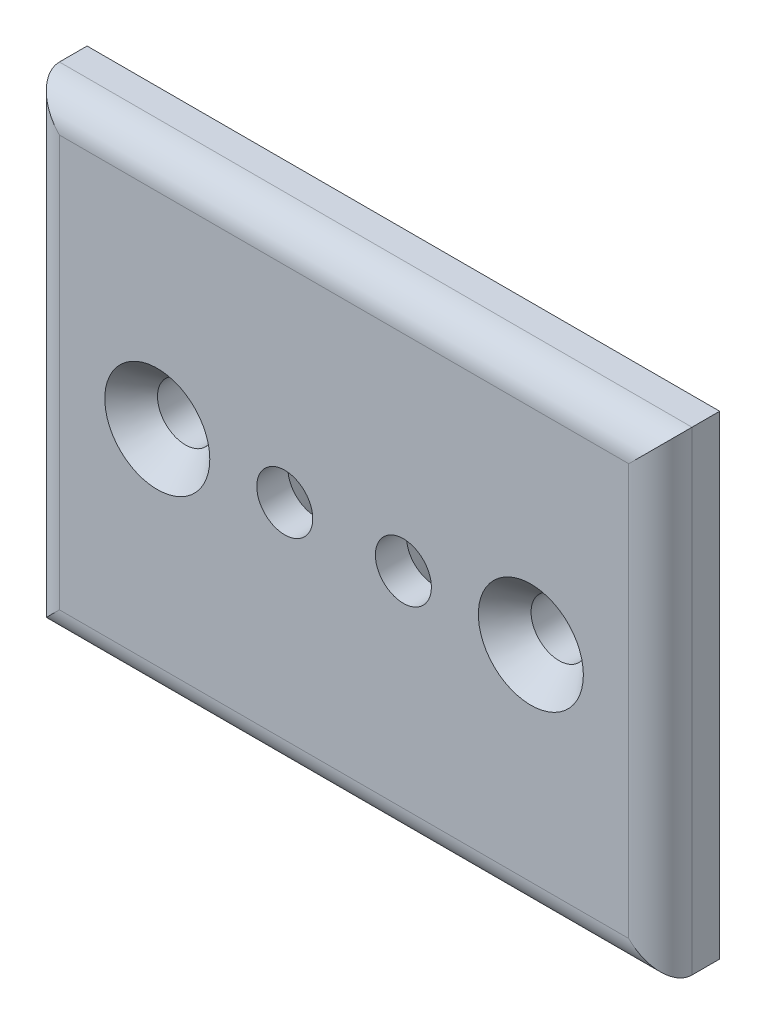
SolidWorks part; units mm, degrees
material "6061 Alloy"
ref_plane "Front Plane" through (0, 0, 0) normal (0, 0, 1) x (1, 0, 0)
ref_plane "Top Plane" through (0, 0, 0) normal (0, 1, 0) x (1, 0, 0)
ref_plane "Right Plane" through (0, 0, 0) normal (1, 0, 0) x (0, 0, -1)
sketch "Sketch1" plane through (0, 0, 0) normal (0, 0, 1) x (1, 0, 0)
  line L0 (-25.4, 19.05) -> (25.4, 19.05)
  line L1 (-25.4, 19.05) -> (-25.4, -19.05)
  line L2 (-25.4, -19.05) -> (25.4, -19.05)
  line L3 (25.4, 19.05) -> (25.4, -19.05)
  line L4 (-25.4, 19.05) -> (25.4, -19.05) construction
  line L5 (-25.4, -19.05) -> (25.4, 19.05) construction
  point P0 (0, 0)
  dimension "D1" = 50.8
  dimension "D2" = 38.1
extrude "Body" add sketch "Sketch1" along normal blind 4.7625
hole_wizard "CSK for #8 Flat Head Machine Screw1" positions "3DSketch1" profile "Sketch2" countersink size "#8" standard "Ansi Inch" end condition through all
sketch3d "3DSketch1"
  line L3 (-25.4, 0, 4.7625) -> (25.4, 0, 4.7625) construction
  line L6 (-15, 19.05, 4.7625) -> (-15, -19.05, 4.7625) construction
  line L9 (15, 19.05, 4.7625) -> (15, -19.05, 4.7625) construction
  line L10 (0, 19.05, 4.7625) -> (0, -19.05, 4.7625) construction
  line L11 (25.4, 19.05, 4.7625) -> (-25.4, 19.05, 4.7625) construction
  line L12 (-25.4, -19.05, 4.7625) -> (25.4, -19.05, 4.7625) construction
  line L14 (-25.4, 19.05, 4.7625) -> (-25.4, -19.05, 4.7625) construction
  line L15 (25.4, -19.05, 4.7625) -> (25.4, 19.05, 4.7625) construction
  point P0 (-15, 0, 4.7625)
  point P2 (15, 0, 4.7625)
  dimension "D1" = 15
  dimension "D2" = 15
sketch "Sketch2" plane through (-15, 0, 4.7625) normal (1, 0, 0) x (0, -1, 0)
  line L0 (0, 0) -> (0, 4.7625)
  line L1 (0, 4.7625) -> (2.2479, 4.7625)
  line L2 (2.2479, 4.7625) -> (2.2479, 2.2645)
  line L3 (2.2479, 2.2645) -> (4.2164, 0)
  line L5 (4.2164, 0) -> (0, 0)
  line L6 (-2.2479, 2.2645) -> (-4.2164, 0) construction
  line L11 (0, -6.35) -> (0, 107.95) construction
  dimension "Thru Hole Dia." = 4.4958
  dimension "Thru Hole Depth" = 4.7625
  dimension "Near C'Sink Dia." = 8.4328
  dimension "Near C'Sink Angle" = 82
hole_wizard "CSK for #8 Flat Head Machine Screw2" positions "3DSketch2" profile "Sketch3" countersink size "#8" standard "Ansi Inch" end condition through all
sketch3d "3DSketch2"
  line L0 (25.4, 0, 0) -> (-25.4, 0, 0) construction
  line L1 (25.4, -19.05, 0) -> (25.4, 19.05, 0) construction
  line L2 (-25.4, 19.05, 0) -> (-25.4, -19.05, 0) construction
  line L5 (25.4, 19.05, 0) -> (-25.4, 19.05, 0) construction
  line L8 (4.7625, 19.05, 0) -> (4.7625, -19.05, 0) construction
  line L9 (-4.7625, 19.05, 0) -> (-4.7625, -19.05, 0) construction
  line L11 (-25.4, -19.05, 0) -> (25.4, -19.05, 0) construction
  line L12 (0, 19.05, 0) -> (0, -19.05, 0) construction
  point P39 (4.7625, 0, 0)
  point P41 (-4.7625, 0, 0)
  dimension "D1" = 4.7625
  dimension "D2" = 4.7625
sketch "Sketch3" plane through (4.7625, 0, 0) normal (1, 0, 0) x (0, 1, 0)
  line L0 (0, 0) -> (0, 4.7625)
  line L1 (0, 4.7625) -> (2.2479, 4.7625)
  line L2 (2.2479, 4.7625) -> (2.2479, 2.2645)
  line L3 (2.2479, 2.2645) -> (4.2164, 0)
  line L5 (4.2164, 0) -> (0, 0)
  line L6 (-2.2479, 2.2645) -> (-4.2164, 0) construction
  line L11 (0, -6.35) -> (0, 107.95) construction
  dimension "Thru Hole Dia." = 4.4958
  dimension "Thru Hole Depth" = 4.7625
  dimension "Near C'Sink Dia." = 8.4328
  dimension "Near C'Sink Angle" = 82
fillet "Fillet1" radius 2.54 4 edges at (0, 19.05, 4.7625) (25.4, 0, 4.7625) (0, -19.05, 4.7625) (-25.4, 0, 4.7625)
